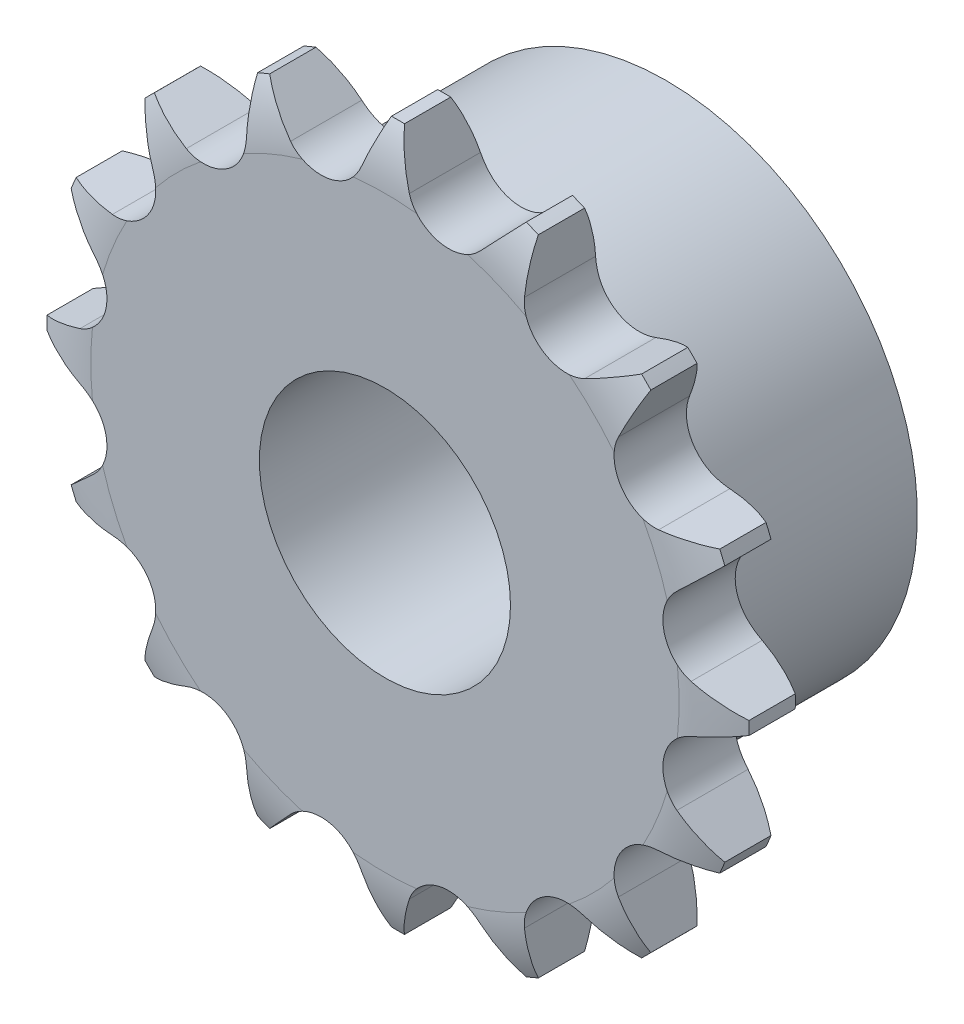
SolidWorks part; units mm, degrees
ref_plane "前视基准面" through (0, 0, 0) normal (0, 0, 1) x (1, 0, 0)
ref_plane "上视基准面" through (0, 0, 0) normal (0, 1, 0) x (1, 0, 0)
ref_plane "右视基准面" through (0, 0, 0) normal (1, 0, 0) x (0, 0, -1)
sketch "草图1" plane through (0, 0, 0) normal (1, 0, 0) x (0, 0, -1)
  line L0 (0, 0) -> (-28, 0) construction
  line L1 (0, 0) -> (0, 25)
  line L2 (0, 25) -> (-20.8, 25)
  line L3 (-28, 6) -> (0, 6)
  line L4 (-22.1, 34.95) -> (-28, 34.95)
  line L5 (-28, 34.95) -> (-28, 0)
  line L6 (-28, 32.55) -> (-20.8, 32.55) construction
  line L8 (-24.4, 32.55) -> (-24.4, 34.95) construction
  line L9 (-20.8, 32.55) -> (-20.8, 25)
  line L10 (-21, 25) -> (-21, 32.55)
  arc A0 (-20.8, 29.2834) -> (-22.1, 34.95) centre (-33.8, 29.2834) ccw
  arc A1 (-21, 29.2834) -> (-22.3, 34.95) centre (-34, 29.2834) ccw
  point P14 (-28, 8)
  point P15 (-21, 25)
  point P17 (-7, 25)
  point P18 (6.9, 25)
  dimension "D1" = 12
  dimension "r" = 13
  dimension "D3" = 13
  dimension "B1" = 7.2
  dimension "D2" = 1.3
  dimension "A" = 28
  dimension "de" = 69.9
  dimension "Dp" = 65.1
  dimension "Dm" = 50
  dimension "C" = 1.3
  dimension "Z" = 16
  dimension "(b1)" = 7
  dimension "B2" = 21
  dimension "B3" = 34.9
sketch "草图3" plane through (0, 0, 0) normal (0, 0, 1) x (1, 0, 0)
  line L0 (0, 0) -> (0, 34.95) construction
  line L1 (0, 0) -> (6.35, 31.9246) construction
  line L2 (0.65, 34.944) -> (2.3727, 30.4125)
  line L3 (0, 28.8493) -> (11.0398, 26.6534) construction
  line L4 (9.4459, 29.0056) -> (12.7716, 32.5329)
  line L5 (-0.65, 34.944) -> (-2.3727, 30.4125) construction
  line L6 (0, 34.95) -> (0, 0) construction
  circle A0 centre (0, 0) radius 34.95 construction
  circle A1 centre (6.35, 31.9246) radius 4.255
  circle A2 centre (-6.35, 31.9246) radius 4.255 construction
  circle A3 centre (0, 0) radius 36.805 construction
  point P13 (-12.7716, 32.5329)
  point P15 (5.5199, 27.7514)
  dimension "D1" = 8.51
  dimension "D3" = 73.61
  dimension "D4" = 1.3
  dimension "D2" = 12.7
sketch "草图4" plane through (0, 0, 0) normal (1, 0, 0) x (0, 0, -1)
  line L1 (-24.4, 32.55) -> (-24.4, 34.95) construction
  line L2 (-24.4, 32.55) -> (-24.4, 34.95) construction
  line L3 (0, 25) -> (-20.8, 25)
  line L4 (0, 0) -> (0, 25) construction
  line L6 (0, 6) -> (0, 25)
  line L8 (-28, 34.95) -> (-28, 0) construction
  line L9 (-22.1, 34.95) -> (-28, 34.95) construction
  line L10 (-20.8, 32.55) -> (-20.8, 25) construction
  line L11 (-28, 6) -> (0, 6) construction
  line L12 (-28, 6) -> (0, 6)
  line L14 (-28, 29.2834) -> (-28, 6)
  line L15 (-22.1, 34.95) -> (-26.7, 34.95)
  line L16 (-20.8, 29.2834) -> (-20.8, 25)
  arc A0 (-28, 29.2834) -> (-26.7, 34.95) centre (-15, 29.2834) cw
  arc A1 (-20.8, 29.2834) -> (-22.1, 34.95) centre (-33.8, 29.2834) ccw construction
  arc A2 (-20.8, 29.2834) -> (-22.1, 34.95) centre (-33.8, 29.2834) ccw
revolve "旋转1" add sketch "草图4" angle 360 about L0
sketch "草图5" plane through (0, 0, 0) normal (0, 0, 1) x (1, 0, 0)
  line L0 (0.65, 34.944) -> (2.3727, 30.4125) construction
  line L1 (9.4459, 29.0056) -> (12.7716, 32.5329) construction
  line L2 (0.65, 34.944) -> (2.3727, 30.4125)
  line L3 (9.4459, 29.0056) -> (12.7716, 32.5329)
  circle A0 centre (6.35, 31.9246) radius 4.255 construction
  arc A1 (2.3727, 30.4125) -> (9.4459, 29.0056) centre (6.35, 31.9246) ccw
  circle A2 centre (0, 0) radius 34.95 construction
  arc A3 (12.7716, 32.5329) -> (0.65, 34.944) centre (0, 0) ccw
extrude "切除-拉伸1" cut sketch "草图5" along normal through all
pattern_circular "阵列(圆周)1" count 16 over 360 about axis through (0, 0, 0) along (0, 0, 1) of "切除-拉伸1"
sketch "草图9" [suppressed] plane through (0, 0, 0) normal (1, 0, 0) x (0, 0, -1)
  line L1 (-34.1, 45.05) -> (-40, 45.05) construction
  line L5 (-40, 45.05) -> (-40, 0) construction
  line L6 (-33, 35) -> (-33, 42.61) construction
  line L7 (-34.3, 45.05) -> (-38.7, 45.05)
  line L8 (-40, 39.3834) -> (-40, 35)
  line L10 (-33, 35) -> (-33, 39.3834)
  line L11 (-33, 39.3834) -> (-40, 39.3834) construction
  line L12 (-36.5, 39.3834) -> (-36.5, 45.05) construction
  line L14 (-33, 35) -> (-40, 35)
  arc A0 (-33, 39.3834) -> (-34.3, 45.05) centre (-46, 39.3834) ccw construction
  arc A1 (-33, 39.3834) -> (-34.3, 45.05) centre (-46, 39.3834) ccw
  arc A2 (-40, 39.3834) -> (-38.7, 45.05) centre (-27, 39.3834) cw
revolve "旋转3" [suppressed] add sketch "草图9" angle 360 about L0
sketch "草图10" [suppressed] plane through (0, 0, 0) normal (1, 0, 0) x (0, 0, -1)
  line L0 (0, 35) -> (-32.8, 35) construction
  line L1 (0, 35) -> (-40, 35)
  line L2 (0, 0) -> (0, 35) construction
  line L3 (-40, 8) -> (0, 8) construction
  line L4 (0, 8) -> (0, 35)
  line L5 (-40, 8) -> (0, 8)
  line L6 (-33, 35) -> (-33, 8) construction
  line L7 (-40, 45.05) -> (-40, 0) construction
  line L11 (-40, 35) -> (-40, 8)
revolve "旋转4" [suppressed] add sketch "草图10" angle 360 about L0
sketch "草图8" [suppressed] plane through (0, 0, 0) normal (0, 0, 1) x (1, 0, 0)
  line L0 (0.65, 45.0453) -> (2.3851, 40.5901) construction
  line L1 (9.6837, 39.4901) -> (12.6548, 43.2361) construction
  line L2 (0.65, 45.0453) -> (2.3851, 40.5901)
  line L3 (9.6837, 39.4901) -> (12.6548, 43.2361)
  circle A0 centre (6.35, 42.1342) radius 4.255 construction
  arc A1 (2.3851, 40.5901) -> (9.6837, 39.4901) centre (6.35, 42.1342) ccw
  circle A2 centre (0, 0) radius 45.05 construction
  arc A3 (12.6548, 43.2361) -> (0.65, 45.0453) centre (0, 0) ccw
extrude "切除-拉伸3" [suppressed] cut sketch "草图8" along normal through all
pattern_circular "阵列(圆周)3" [suppressed] count 16 over 360
pattern_linear "阵列(线性)7" [suppressed] count 2 spacing 14 along (0, 0, 1)
sketch "草图11" [suppressed] plane through (0, 0, 0) normal (1, 0, 0) x (0, 0, -1)
  line L0 (-50, 24.95) -> (-50, 0) construction
  line L1 (-50, 24.95) -> (-50, 8) construction
  line L2 (-44.1, 24.95) -> (-50, 24.95) construction
  line L3 (0, 16) -> (-42.8, 16) construction
  line L4 (-43, 19.2675) -> (-50, 19.2675) construction
  line L5 (0, 0) -> (0, 16) construction
  line L7 (-44.1, 24.95) -> (-50, 24.95) construction
  line L8 (-46.5, 19.2675) -> (-46.5, 24.95) construction
  line L9 (-50, 8) -> (0, 8) construction
  line L10 (0, 8) -> (0, 16) construction
  line L11 (-50, 8) -> (0, 8)
  line L16 (-43, 16) -> (-43, 19.2834) construction
  line L17 (0, 16) -> (0, 8)
  line L18 (-43, 16) -> (-43, 22.535) construction
  line L23 (-50, 16) -> (-50, 8)
  line L25 (0, 16) -> (-50, 16)
  arc A3 (-43, 19.2834) -> (-44.3, 24.95) centre (-56, 19.2834) ccw construction
  arc A5 (-43, 19.2834) -> (-44.3, 24.95) centre (-56, 19.2834) ccw construction
revolve "旋转5" [suppressed] add sketch "草图11" angle 360 about L0
sketch "草图12" [suppressed] plane through (0, 0, 0) normal (1, 0, 0) x (0, 0, -1)
  line L0 (-43, 16) -> (-43, 22.535) construction
  line L1 (-43, 19.2834) -> (-50, 19.2834) construction
  line L2 (-44.1, 24.95) -> (-50, 24.95) construction
  line L3 (-50, 24.95) -> (-50, 0) construction
  line L5 (-43, 16) -> (-43, 19.2834)
  line L6 (-46.5, 19.2834) -> (-46.5, 24.95) construction
  line L7 (-43, 16) -> (-50, 16)
  line L8 (-44.3, 24.95) -> (-48.7, 24.95)
  line L9 (-50, 19.2834) -> (-50, 16)
  arc A0 (-43, 19.2834) -> (-44.3, 24.95) centre (-56, 19.2834) ccw construction
  arc A1 (-50, 19.2834) -> (-48.7, 24.95) centre (-37, 19.2834) cw
  arc A3 (-43, 19.2834) -> (-44.3, 24.95) centre (-56, 19.2834) ccw
revolve "旋转6" [suppressed] add sketch "草图12" angle 360 about L0
sketch "草图13" [suppressed] plane through (0, 0, 0) normal (0, 0, 1) x (1, 0, 0)
  line L0 (0.65, 24.9415) -> (2.3419, 20.1936) construction
  line L1 (0.65, 24.9415) -> (2.3419, 20.1936)
  line L2 (8.9493, 18.2531) -> (12.9399, 21.3322) construction
  line L3 (8.9493, 18.2531) -> (12.9399, 21.3322)
  circle A0 centre (6.35, 21.6218) radius 4.255 construction
  arc A1 (2.3419, 20.1936) -> (8.9493, 18.2531) centre (6.35, 21.6218) ccw
  circle A2 centre (0, 0) radius 24.95 construction
  arc A3 (12.9399, 21.3322) -> (0.65, 24.9415) centre (0, 0) ccw
extrude "切除-拉伸4" [suppressed] cut sketch "草图13" along normal through all
pattern_circular "阵列(圆周)4" [suppressed] count 16 over 360
pattern_linear "阵列(线性)9" [suppressed] count 3 spacing 13.95 along (0, 0, 1)
sketch "草图14" plane through (0, 0, 28) normal (0, 0, 1) x (1, 0, 0)
  circle A0 centre (0, 0) radius 12.5
extrude "切除-拉伸5" cut sketch "草图14" against normal blind 46
